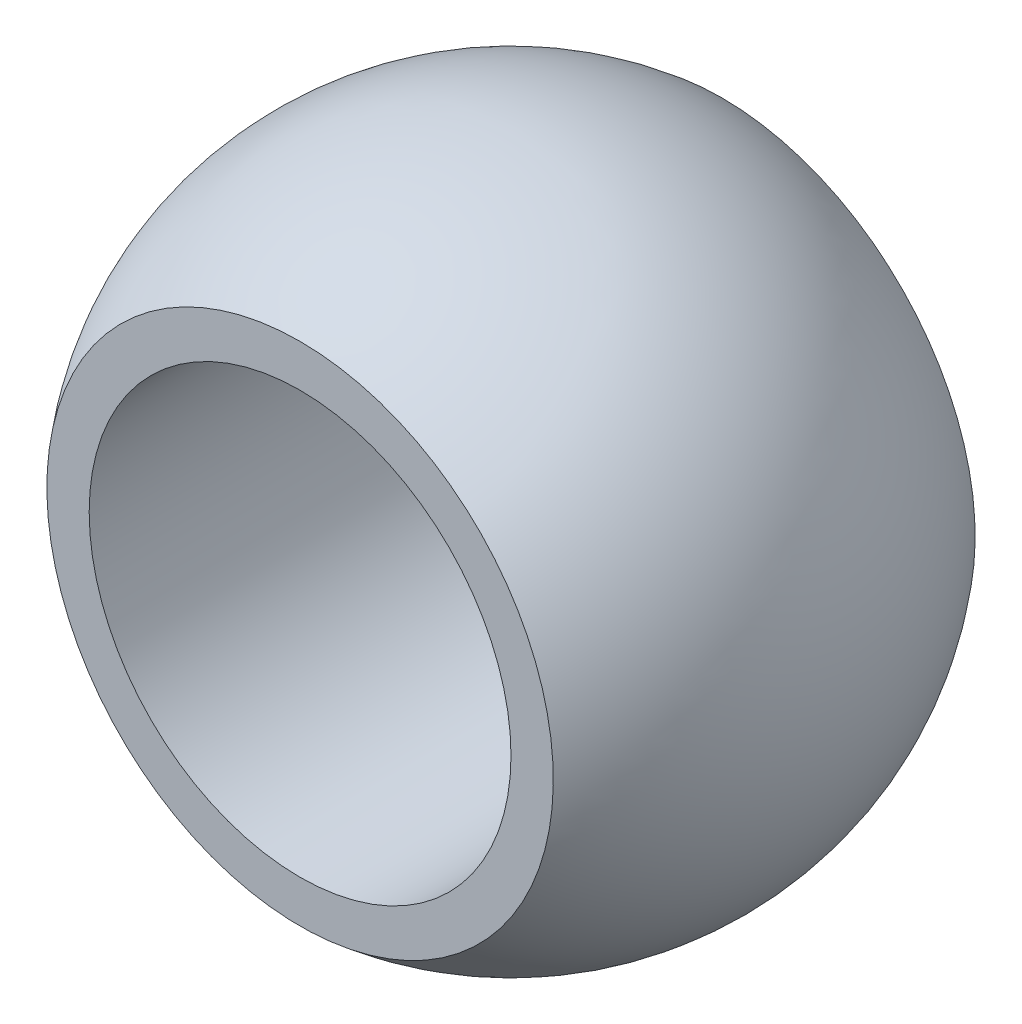
SolidWorks part; units mm, degrees
ref_plane "Front Plane" through (0, 0, 0) normal (0, 0, 1) x (1, 0, 0)
ref_plane "Top Plane" through (0, 0, 0) normal (0, 1, 0) x (1, 0, 0)
ref_plane "Right Plane" through (0, 0, 0) normal (1, 0, 0) x (0, 0, -1)
sketch "Sketch2" plane through (0, 0, 0) normal (1, 0, 0) x (0, 0, -1)
  line L0 (-4, 0) -> (0, 0) construction
  line L1 (0, 0) -> (4, 0) construction
  line L2 (0, 0) -> (0, 6.25) construction
  line L3 (-4, 4) -> (4, 4)
  line L4 (-4, 4.8023) -> (-4, 4)
  line L5 (4, 4.8023) -> (4, 4)
  arc A1 (4, 4.8023) -> (-4, 4.8023) centre (0, 0) ccw
  point P7 (0, 0)
  point P9 (0, 6.25)
  point P10 (-4, 0)
  point P13 (0, 4)
  dimension "D1" = 6.25
  dimension "D2" = 8
  dimension "D3" = 8
revolve "Revolve1" add sketch "Sketch2" angle 360 about L0
